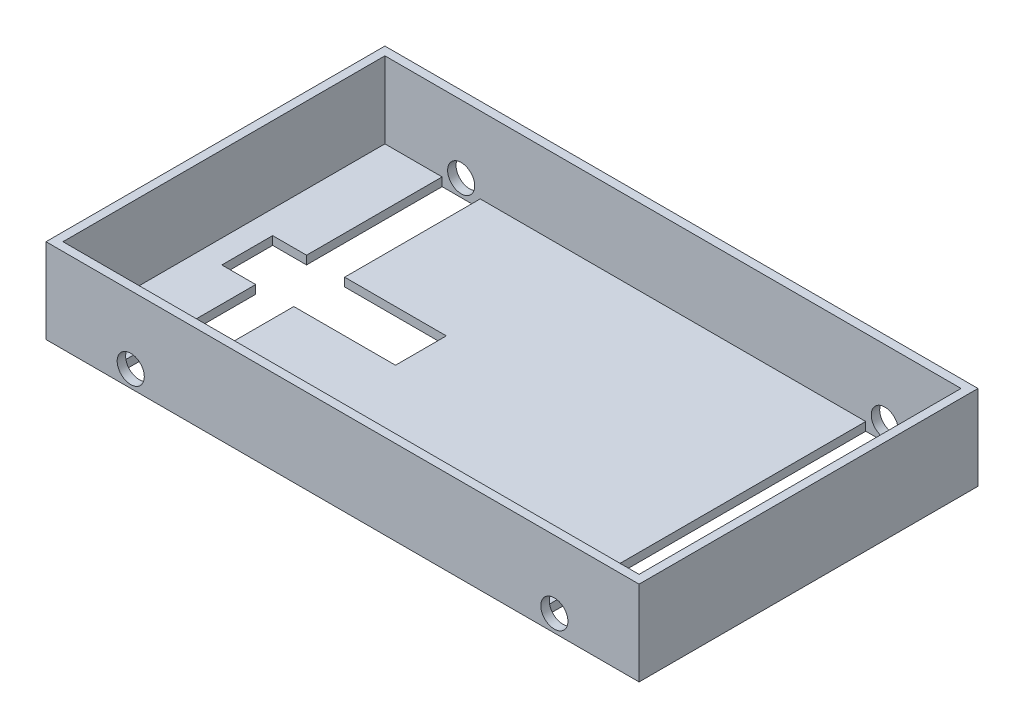
SolidWorks part; units mm, degrees
ref_plane "Front Plane" through (0, 0, 0) normal (0, 0, 1) x (1, 0, 0)
ref_plane "Top Plane" through (0, 0, 0) normal (0, 1, 0) x (1, 0, 0)
ref_plane "Right Plane" through (0, 0, 0) normal (1, 0, 0) x (0, 0, -1)
sketch "Sketch1" plane through (0, 0, 0) normal (0, 1, 0) x (1, 0, 0)
  line L1 (175, -100) -> (-175, -100)
  line L2 (175, -100) -> (175, 100)
  line L3 (175, 100) -> (-175, 100)
  line L4 (-175, -100) -> (-175, 100)
  line L5 (175, -100) -> (-175, 100) construction
  line L6 (175, 100) -> (-175, -100) construction
  point P0 (0, 0)
  dimension "D1" = 200
  dimension "D2" = 350
extrude "Boss-Extrude1" add sketch "Sketch1" along normal blind 50 contours L1 L4 L3 L2
shell "Shell1" thickness 5
sketch "Sketch3" plane through (0, 0, 100) normal (0, 0, 1) x (1, 0, 0)
  line L0 (0, -27.5) -> (0, 27.5) construction
  circle A0 centre (-125, 10) radius 8
  circle A1 centre (125, 10) radius 8
  dimension "D1" = 16
  dimension "D2" = 10
  dimension "D3" = 125
extrude "Cut-Extrude1" cut sketch "Sketch3" against normal up to surface (200 mm away) up to face at (0, 25, -100)
sketch "Sketch4" plane through (0, 5, 0) normal (0, 1, 0) x (1, 0, 0)
  line L0 (-136.245, 95) -> (-136.245, -95)
  line L1 (-170, 95) -> (170, 95)
  line L2 (-170, 95) -> (-170, -95)
  line L3 (-170, -95) -> (170, -95)
  line L4 (170, 95) -> (170, -95)
  line L5 (-131.245, 95) -> (-131.245, -95) construction
  line L6 (-113.755, 95) -> (-113.755, -95)
  line L7 (-118.755, -95) -> (-118.755, 95) construction
  line L8 (0, -27.5) -> (0, 27.5) construction
  line L9 (113.755, 95) -> (113.755, -95)
  line L10 (136.245, 95) -> (136.245, -95)
  line M2 (-118.755, 95) -> (-118.755, -95)
  line M3 (-118.755, -95) -> (118.755, -95)
  line M4 (118.755, -95) -> (118.755, 95)
  line M5 (118.755, 95) -> (-118.755, 95)
  dimension "D1" = 5
  dimension "D2" = 5
extrude "Cut-Extrude4" cut sketch "Sketch4" against normal blind 10 contours L0 L3 L1 M2 | L6 L1 M2 M3 | L9 M5 M3 M4 | L10 L1 L3 M4
sketch "Sketch5" plane through (0, 5, 0) normal (0, 1, 0) x (1, 0, 0)
  line L5 (-136.245, 95) -> (-136.245, -95) construction
  line L6 (-156.245, 15) -> (-53.755, 15)
  line L7 (-156.245, 15) -> (-156.245, -15)
  line L8 (-156.245, -15) -> (-53.755, -15)
  line L9 (-53.755, 15) -> (-53.755, -15)
  line L11 (-113.755, 95) -> (-113.755, -95) construction
  point P4 (-53.755, 0)
  point P9 (-136.245, 0)
  dimension "D1" = 60
  dimension "D2" = 20
  dimension "D3" = 30
extrude "Cut-Extrude5" cut sketch "Sketch5" against normal blind 10
